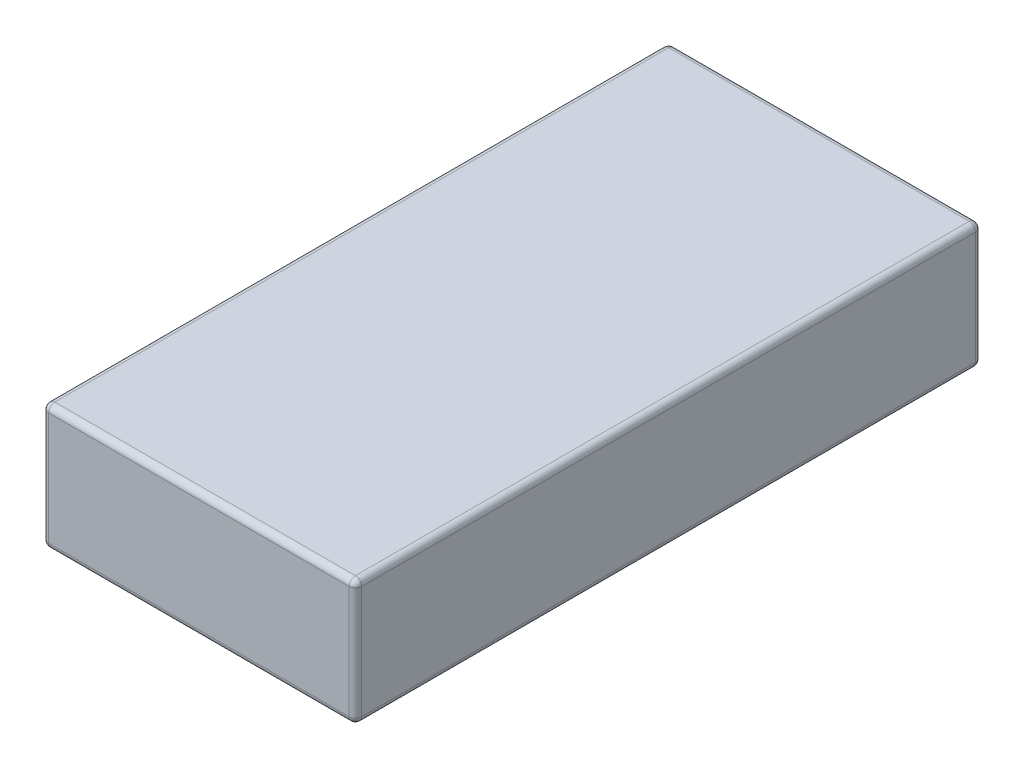
SolidWorks part; units mm, degrees
material "Chrome Stainless Steel"
ref_plane "Front Plane" through (0, 0, 0) normal (0, 0, 1) x (1, 0, 0)
ref_plane "Top Plane" through (0, 0, 0) normal (0, 1, 0) x (1, 0, 0)
ref_plane "Right Plane" through (0, 0, 0) normal (1, 0, 0) x (0, 0, -1)
sketch "Sketch1" plane through (0, 0, 0) normal (0, 1, 0) x (1, 0, 0)
  line L1 (-2.5, 5) -> (2.5, 5)
  line L2 (-2.5, 5) -> (-2.5, -5)
  line L3 (-2.5, -5) -> (2.5, -5)
  line L4 (2.5, 5) -> (2.5, -5)
  line L5 (-2.5, 5) -> (2.5, -5) construction
  line L6 (-2.5, -5) -> (2.5, 5) construction
  point P0 (0, 0)
  dimension "D1" = 5
  dimension "D2" = 10
extrude "Boss-Extrude1" add sketch "Sketch1" along normal blind 2
fillet "Fillet1" radius 0.1 12 edges at (2.5, 0, 0) (2.5, 1, -5) (0, 0, -5) (-2.5, 1, -5) (-2.5, 0, 0) (-2.5, 1, 5) (2.5, 1, 5) (0, 0, 5) (0, 2, 5) (-2.5, 2, 0) (0, 2, -5) (2.5, 2, 0)
